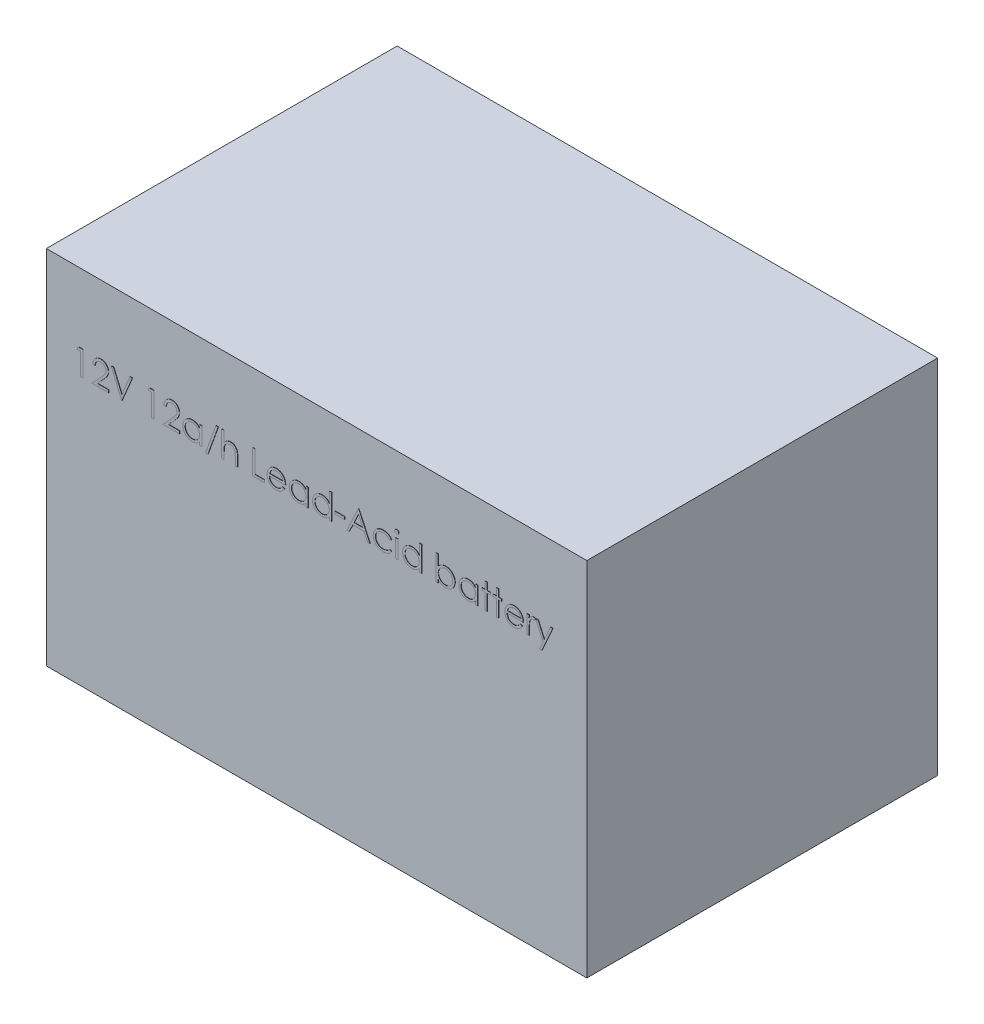
SolidWorks part; units mm, degrees
material "1060 Alloy"
ref_plane "Front Plane" through (0, 0, 0) normal (0, 0, 1) x (1, 0, 0)
ref_plane "Top Plane" through (0, 0, 0) normal (0, 1, 0) x (1, 0, 0)
ref_plane "Right Plane" through (0, 0, 0) normal (1, 0, 0) x (0, 0, -1)
sketch "Sketch1" plane through (0, 0, 0) normal (0, 1, 0) x (1, 0, 0)
  line L1 (-29.9215, 9.3063) -> (121.0785, 9.3063)
  line L2 (-29.9215, 9.3063) -> (-29.9215, -88.6937)
  line L3 (-29.9215, -88.6937) -> (121.0785, -88.6937)
  line L4 (121.0785, 9.3063) -> (121.0785, -88.6937)
  dimension "D1" = 151
  dimension "D2" = 98
extrude "Boss-Extrude1" add sketch "Sketch1" along normal blind 101
sketch "Sketch2" plane through (0, 0, 88.6937) normal (0, 0, 1) x (1, 0, 0)
  text T0 "12V 12a/h Lead-Acid battery" font "Century Gothic" height in points 26
extrude "Boss-Extrude2" add sketch "Sketch2" along normal blind 0.1
